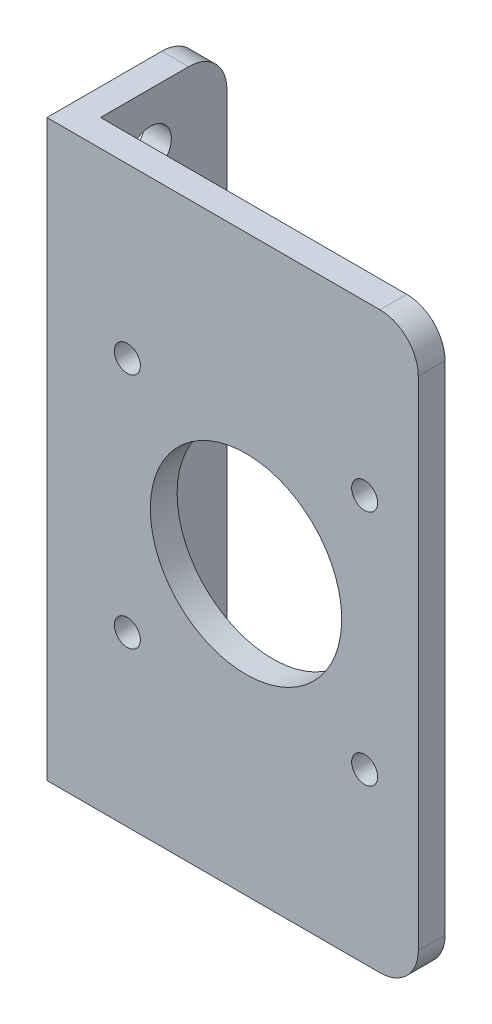
SolidWorks part; units mm, degrees
ref_plane "Front Plane" through (0, 0, 0) normal (0, 0, 1) x (1, 0, 0)
ref_plane "Top Plane" through (0, 0, 0) normal (0, 1, 0) x (1, 0, 0)
ref_plane "Right Plane" through (0, 0, 0) normal (1, 0, 0) x (0, 0, -1)
sketch "Sketch1" plane through (0, 0, 0) normal (0, 1, 0) x (1, 0, 0)
  line L0 (0, 0) -> (0, 20)
  line L1 (0, 20) -> (3.5, 20)
  line L2 (3.5, 20) -> (3.5, 3.5)
  line L3 (3.5, 3.5) -> (48.5, 3.5)
  line L4 (48.5, 3.5) -> (48.5, 0)
  line L5 (48.5, 0) -> (0, 0)
  dimension "D1" = 3.5
  dimension "D2" = 45
  dimension "D3" = 20
extrude "Boss-Extrude1" add sketch "Sketch1" along normal mid plane 75
hole_wizard "M3 Clearance Hole1" positions "Sketch2" profile "Sketch3" hole size "M3" standard "ANSI Metric" end condition through all
sketch "Sketch2" plane through (0, 0, -3.5) normal (0, 0, -1) x (-1, 0, 0)
  line L0 (-41.5, -15.5) -> (-41.5, 15.5) construction
  line L1 (-41.5, 15.5) -> (-10.5, 15.5) construction
  line L2 (-10.5, 15.5) -> (-10.5, -15.5) construction
  line L3 (-10.5, -15.5) -> (-41.5, -15.5) construction
  line L5 (-26, 15.5) -> (-26, 37.5) construction
  line L6 (-48.5, 37.5) -> (-3.5, 37.5) construction
  line L8 (-41.5, 0) -> (-48.5, 0) construction
  line L9 (-48.5, 37.5) -> (-48.5, -37.5) construction
  point P0 (-41.5, 15.5)
  point P2 (-10.5, 15.5)
  point P4 (-10.5, -15.5)
  point P6 (-41.5, -15.5)
  dimension "D1" = 31
sketch "Sketch3" plane through (41.5, 15.5, -3.5) normal (1, 0, 0) x (0, 1, 0)
  line L0 (0, 0) -> (0, 3.5)
  line L1 (0, 3.5) -> (1.7, 3.5)
  line L2 (1.7, 3.5) -> (1.7, 0)
  line L5 (1.7, 0) -> (0, 0)
  line L11 (0, -6.35) -> (0, 107.95) construction
  dimension "Thru Hole Dia." = 3.4
  dimension "Thru Hole Depth" = 3.5
sketch "Sketch4" plane through (0, 0, -3.5) normal (0, 0, -1) x (-1, 0, 0)
  line L0 (-26, 0) -> (-26, 37.5) construction
  line L1 (-48.5, 37.5) -> (-3.5, 37.5) construction
  line L2 (-26, 0) -> (-48.5, 0) construction
  line L3 (-48.5, 37.5) -> (-48.5, -37.5) construction
  circle A0 centre (-26, 0) radius 12.5
  dimension "D1" = 25
extrude "Cut-Extrude1" cut sketch "Sketch4" against normal through all
hole_wizard "M5 Clearance Hole1" positions "Sketch5" profile "Sketch6" hole size "M5" standard "ANSI Metric" end condition through all
sketch "Sketch5" plane through (0, 0, 0) normal (-1, 0, 0) x (0, 0, 1)
  line L0 (-10, 30.5) -> (-10, -30.5) construction
  line L2 (0, 37.5) -> (0, -37.5) construction
  line L3 (-10, 0) -> (0, 0) construction
  line L4 (-20, 37.5) -> (0, 37.5) construction
  point P0 (-10, 30.5)
  point P2 (-10, -30.5)
  dimension "D1" = 10
  dimension "D2" = 7
sketch "Sketch6" plane through (0, 30.5, -10) normal (0, 1, 0) x (0, 0, 1)
  line L0 (0, 0) -> (0, 48.5)
  line L1 (0, 48.5) -> (2.75, 48.5)
  line L2 (2.75, 48.5) -> (2.75, 0)
  line L5 (2.75, 0) -> (0, 0)
  line L11 (0, -6.35) -> (0, 107.95) construction
  dimension "Thru Hole Dia." = 5.5
  dimension "Thru Hole Depth" = 48.5
fillet "Fillet1" radius 5 4 edges at (1.75, -37.5, -20) (1.75, 37.5, -20) (48.5, -37.5, -1.75) (48.5, 37.5, -1.75)
ref_plane "Plane1" through (0, 0, -10) normal (0, 0, 1) x (1, 0, 0)
